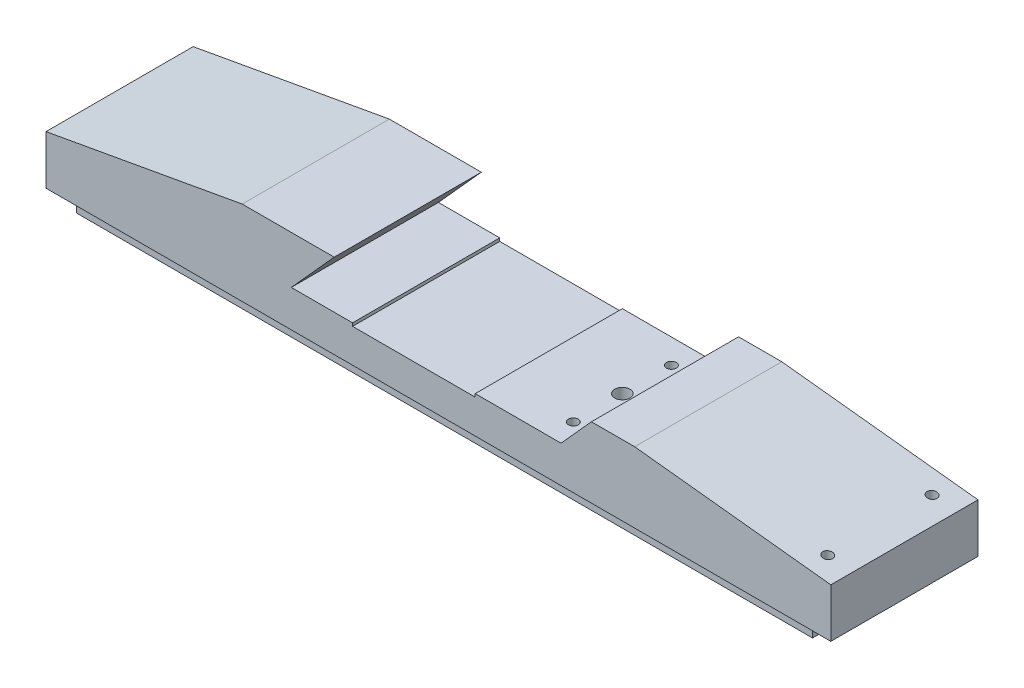
SolidWorks part; units mm, degrees
material "Gray Cast Iron"
ref_plane "Front" through (0, 0, 0) normal (0, 0, 1) x (1, 0, 0)
ref_plane "Top" through (0, 0, 0) normal (0, 1, 0) x (1, 0, 0)
ref_plane "Right" through (0, 0, 0) normal (1, 0, 0) x (0, 0, -1)
sketch "Sketch2" plane through (0, 0, 0) normal (0, 0, 1) x (1, 0, 0)
  line L0 (0, 0) -> (406.4, 0)
  line L1 (406.4, 0) -> (406.4, 44.5262)
  line L2 (406.4, 44.5262) -> (304.8, 55.6387)
  line L3 (304.8, 55.6387) -> (282.4233, 55.6387)
  line L4 (282.4233, 55.6387) -> (266.7, 38.1762)
  line L5 (266.7, 38.1762) -> (222.25, 38.1762)
  line L6 (222.25, 38.1762) -> (222.25, 36.5887)
  line L7 (222.25, 36.5887) -> (158.75, 36.5887)
  line L8 (158.75, 36.5887) -> (158.75, 38.1762)
  line L9 (158.75, 38.1762) -> (127, 38.1762)
  line L10 (127, 38.1762) -> (149.225, 62.8596)
  line L11 (149.225, 62.8596) -> (101.6, 62.8596)
  line L12 (101.6, 62.8596) -> (0, 44.5516)
  line L13 (0, 44.5516) -> (0, 0)
  dimension "D1" = 44.5516
  dimension "D2" = 127
  dimension "D3" = 48
  dimension "D4" = 47.625
  dimension "D5" = 132
  dimension "D6" = 101.6
  dimension "D7" = 406.4
  dimension "D8" = 55.6387
  dimension "D9" = 44.45
  dimension "D10" = 31.75
  dimension "D11" = 38.1762
  dimension "D12" = 101.6
  dimension "D13" = 139.7
  dimension "D14" = 1.5875
  dimension "D15" = 44.5262
extrude "Boss-Extrude1" add sketch "Sketch2" against normal blind 76.2
sketch "Sketch4" plane through (0, 0, 0) normal (0, -1, 0) x (-1, 0, 0)
  line L0 (-406.4, 0) -> (-381, 0)
  line L1 (0, 0) -> (-406.4, 0) construction
  line L2 (-381, 0) -> (-381, 76.2)
  line L3 (0, 76.2) -> (-406.4, 76.2) construction
  line L4 (-381, 76.2) -> (-406.4, 76.2)
  line L5 (-406.4, 76.2) -> (-406.4, 0)
  dimension "D1" = 25.4
extrude "Cut-Extrude2" cut sketch "Sketch4" against normal blind 19.1262
sketch "Sketch7" plane through (0, 0, 0) normal (-1, 0, 0) x (0, 0, 1)
  line L0 (-38.1, 44.5516) -> (-38.1, 0) construction
  line L1 (0, 44.5516) -> (0, 0) construction
  line L2 (-76.2, 19.1516) -> (-76.2, -1.27)
  line L3 (-15.9131, 0.0254) -> (-15.9131, 9.5504)
  line L4 (-60.2869, 0.0254) -> (-60.2869, 9.5504)
  line L5 (-15.9131, 9.5504) -> (-25.4381, 9.5504)
  line L6 (-60.2869, 9.5504) -> (-50.7619, 9.5504)
  line L7 (-25.4381, 9.5504) -> (-25.4381, 19.1516)
  line L8 (-50.7619, 9.5504) -> (-50.7619, 19.1516)
  line L9 (-25.4381, 19.1516) -> (0, 19.1516)
  line L10 (-50.7619, 19.1516) -> (-76.2, 19.1516)
  line L11 (-76.2, -1.27) -> (-60.2869, -1.27)
  line L15 (0, 19.1516) -> (0, -1.27)
  line L18 (-76.2, 44.5516) -> (0, 44.5516) construction
  line L19 (-60.2869, -1.27) -> (-60.2869, 0.0254)
  line L20 (0, -1.27) -> (-15.9131, -1.27)
  line L21 (-15.9131, -1.27) -> (-15.9131, 0.0254)
  line L22 (-76.2, 0) -> (0, 0) construction
  point P7 (-38.1, 0)
  dimension "D1" = 44.3738
  dimension "D2" = 9.6012
  dimension "D3" = 9.525
  dimension "D4" = 9.525
  dimension "D5" = 25.4
  dimension "D6" = 1.27
extrude "Cut-Extrude9" cut sketch "Sketch7" against normal through all
hole_wizard "1/4-20 Tapped Hole1" positions "Sketch9" profile "Sketch8" tap size "1/4-20" standard "ANSI Inch"
sketch "Sketch9" plane through (0, 0, -76.2) normal (0, 0, -1) x (-1, 0, 0)
  line L0 (-266.7, 38.1762) -> (-222.25, 38.1762) construction
  point P0 (-149.225, 28.6512)
  point P2 (-231.775, 28.6512)
  dimension "D1" = 47.625
  dimension "D2" = 82.55
  dimension "D3" = 9.525
sketch "Sketch8" plane through (149.225, 28.6512, -76.2) normal (1, 0, 0) x (0, 1, 0)
  line L0 (0, 0) -> (0, 14.2338)
  line L1 (0, 14.2338) -> (2.5527, 12.7)
  line L2 (2.5527, 12.7) -> (2.5527, 0)
  line L5 (2.5527, 0) -> (0, 0)
  line L10 (0, 14.2338) -> (-2.5527, 12.7) construction
  line L11 (0, -6.35) -> (0, 107.95) construction
  dimension "Tap Drill Dia." = 5.1054
  dimension "Tap Drill Depth" = 12.7
  dimension "Drill Angle" = 118
cosmetic thread "Hole Thread1" parameters "D1"=12.7, "D2"=6.35
cosmetic thread "Hole Thread2" parameters "D1"=12.7, "D2"=6.35
hole_wizard "3/8-16 Tapped Hole1" positions "Sketch11" profile "Sketch10" tap size "3/8-16" standard "ANSI Inch"
sketch "Sketch11" plane through (0, 38.1762, 0) normal (0, 1, 0) x (1, 0, 0)
  line L0 (266.7, 76.2) -> (266.7, 0) construction
  line L1 (266.7, 76.2) -> (222.25, 76.2) construction
  point P0 (260.35, 38.1)
  dimension "D1" = 6.35
  dimension "D2" = 38.1
sketch "Sketch10" plane through (260.35, 38.1762, -38.1) normal (1, 0, 0) x (0, 0, 1)
  line L0 (0, 0) -> (0, 27.7847)
  line L1 (0, 27.7847) -> (3.9687, 25.4)
  line L2 (3.9687, 25.4) -> (3.9687, 0)
  line L5 (3.9687, 0) -> (0, 0)
  line L10 (0, 27.7847) -> (-3.9688, 25.4) construction
  line L11 (0, -6.35) -> (0, 107.95) construction
  dimension "Tap Drill Dia." = 7.9375
  dimension "Tap Drill Depth" = 25.4
  dimension "Drill Angle" = 118
cosmetic thread "Hole Thread3" parameters "D1"=19.05, "D2"=9.525
hole_wizard "1/4-20 Tapped Hole2" positions "Sketch13" profile "Sketch12" tap size "1/4-20" standard "ANSI Inch"
sketch "Sketch13" plane through (0, 38.1762, 0) normal (0, 1, 0) x (1, 0, 0)
  line L0 (266.7, 76.2) -> (222.25, 76.2) construction
  line L1 (266.7, 76.2) -> (266.7, 0) construction
  point P0 (260.35, 63.5)
  point P2 (260.35, 12.7)
  point P5 (244.475, 76.2)
  dimension "D1" = 12.7
  dimension "D2" = 50.8
  dimension "D3" = 6.35
sketch "Sketch12" plane through (260.35, 38.1762, -63.5) normal (1, 0, 0) x (0, 0, 1)
  line L0 (0, 0) -> (0, 12.659)
  line L1 (0, 12.659) -> (2.5527, 11.1252)
  line L2 (2.5527, 11.1252) -> (2.5527, 0)
  line L5 (2.5527, 0) -> (0, 0)
  line L10 (0, 12.659) -> (-2.5527, 11.1252) construction
  line L11 (0, -6.35) -> (0, 107.95) construction
  dimension "Tap Drill Dia." = 5.1054
  dimension "Tap Drill Depth" = 11.1252
  dimension "Drill Angle" = 118
cosmetic thread "Hole Thread4" parameters "D1"=11.1252, "D2"=6.35
cosmetic thread "Hole Thread5" parameters "D1"=11.1252, "D2"=6.35
hole_wizard "1/4-20 Tapped Hole3" positions "Sketch15" profile "Sketch14" tap size "1/4-20" standard "ANSI Inch" end condition through all
sketch "Sketch15" plane through (0, 19.1516, 0) normal (0, -1, 0) x (-1, 0, 0)
  line L0 (-406.4, 0) -> (0, 0) construction
  line L1 (-406.4, 50.7619) -> (-406.4, 76.2) construction
  point P0 (-393.7, 11.1125)
  point P2 (-393.7, 65.0875)
  dimension "D1" = 11.1125
  dimension "D2" = 53.975
  dimension "D3" = 12.7
cosmetic thread "Hole Thread6" parameters "D2"=6.35
cosmetic thread "Hole Thread7" parameters "D2"=6.35
sketch "Sketch14" plane through (393.7, 19.1516, -11.1125) normal (1, 0, 0) x (0, 0, -1)
  line L0 (0, 0) -> (0, 43.708)
  line L1 (0, 43.708) -> (2.5527, 43.708)
  line L2 (2.5527, 43.708) -> (2.5527, 0)
  line L5 (2.5527, 0) -> (0, 0)
  line L11 (0, -6.35) -> (0, 107.95) construction
  dimension "Thru Tap Drill Dia." = 5.1054
  dimension "Thru Tap Drill Depth" = 43.708
